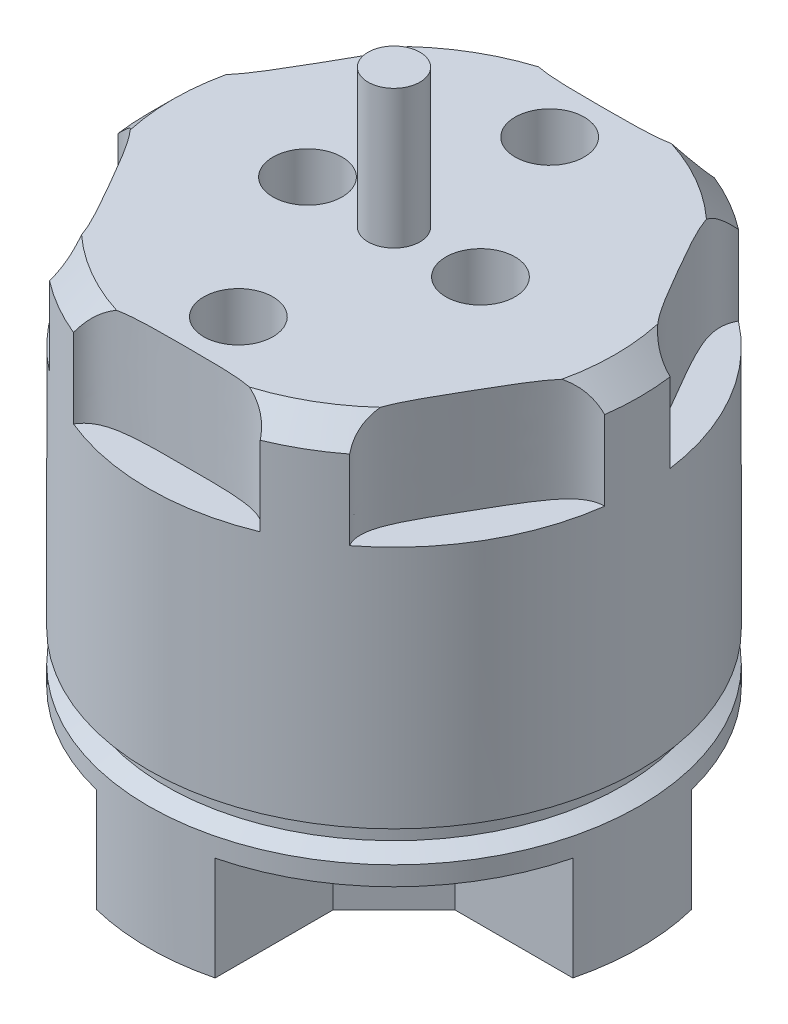
SolidWorks part; units mm, degrees
material "ABS PC"
ref_plane "Front Plane" through (0, 0, 0) normal (0, 0, 1) x (1, 0, 0)
ref_plane "Top Plane" through (0, 0, 0) normal (0, 1, 0) x (1, 0, 0)
ref_plane "Right Plane" through (0, 0, 0) normal (1, 0, 0) x (0, 0, -1)
sketch "Sketch1" plane through (0, 0, 0) normal (1, 0, 0) x (0, 0, -1)
  line L0 (0, 0) -> (0, 18.5) construction
  line L1 (0, 18.5) -> (-0.75, 18.5)
  line L2 (-0.75, 18.5) -> (-0.75, 14.5)
  line L3 (-0.75, 14.5) -> (-6.3929, 14.5)
  line L4 (-7.1, 13.7929) -> (-6.3929, 14.5)
  line L5 (-7.1, 13.7929) -> (-7.1, 14.5) construction
  line L6 (-7.1, 14.5) -> (-6.3929, 14.5) construction
  line L7 (-7.1, 14.5) -> (-6.7464, 14.1464) construction
  line L8 (-7.1, 13.7929) -> (-7.1, 0)
  line L9 (-7.1, 0) -> (-1, 0)
  line L10 (-1, 0) -> (-1, -1)
  line L11 (-1, -1) -> (0, -1)
  line L12 (0, -1) -> (0, 0)
  line L13 (0, 0) -> (0, 18.5)
  point P9 (-1, -0.5)
  dimension "D1" = 1.5
  dimension "D2" = 4
  dimension "D3" = 18.5
  dimension "D4" = 14.2
  dimension "D5" = 0.5
  dimension "D6" = 2
  dimension "D7" = 1
revolve "Revolve1" add sketch "Sketch1" angle 360 about L13
sketch "Sketch2" plane through (0, 0, 0) normal (0, 0, 1) x (1, 0, 0)
  line L0 (-7.1, 4) -> (7.1, 4)
  line L1 (-7.1, 13.7929) -> (-7.1, 0) construction
  line L2 (7.1, 0) -> (7.1, 13.7929) construction
  dimension "D1" = 4
split line "Split Line1"
sketch "Sketch3" plane through (0, 0, 0) normal (0, -1, 0) x (1, 0, 0)
  circle A5 centre (0, 0) radius 4.5 construction
  circle A6 centre (0, 4.5) radius 1
  circle A7 centre (4.5, 0) radius 1
  circle A8 centre (-4.5, 0) radius 1
  circle A9 centre (0, -4.5) radius 1
  dimension "D1" = 2
  dimension "D2" = 9
extrude "Cut-Extrude1" cut sketch "Sketch3" against normal blind 3
sketch "Sketch4" plane through (0, 14.5, 0) normal (0, 1, 0) x (1, 0, 0)
  line L0 (-2.5, 0) -> (0, 0) construction
  line L1 (0, 0) -> (0, 4.5) construction
  circle A0 centre (0, 4.5) radius 1
  circle A1 centre (2.5, 0) radius 1
  circle A2 centre (0, -4.5) radius 1
  circle A3 centre (-2.5, 0) radius 1
  ellipse E0 centre (0, 0) end of major axis (0, 4.5) minor radius 2.5 construction
  dimension "D3" = 2
  dimension "D1" = 5
  dimension "D2" = 9
extrude "Cut-Extrude2" cut sketch "Sketch4" against normal blind 4
sketch "Sketch5" plane through (0, 14.5, 0) normal (0, 1, 0) x (1, 0, 0)
  line L0 (-2.7, 6.5666) -> (-2.0712, 5.5) construction
  line L1 (-2.0712, 5.5) -> (0, 6.5) construction
  line L2 (0, 6.5) -> (2.0712, 5.5) construction
  line L3 (2.0712, 5.5) -> (2.7, 6.5666) construction
  line L4 (0, 0) -> (0, 6.5) construction
  line L5 (-2.0712, 5.5) -> (0, 5.5) construction
  line L6 (0, 5.5) -> (2.0712, 5.5) construction
  line L7 (-2.7, 6.5666) -> (0, 6.5666) construction
  line L8 (0, 6.5666) -> (2.7, 6.5666) construction
  line L9 (4.3368, 5.6216) -> (3.7275, 4.5437) construction
  line L10 (3.7275, 4.5437) -> (5.6292, 3.25) construction
  line L11 (5.6292, 3.25) -> (5.7988, 0.9563) construction
  line L12 (5.7988, 0.9563) -> (7.0368, 0.945) construction
  line L13 (7.0368, -0.945) -> (5.7988, -0.9563) construction
  line L14 (5.7988, -0.9563) -> (5.6292, -3.25) construction
  line L15 (5.6292, -3.25) -> (3.7275, -4.5437) construction
  line L16 (3.7275, -4.5437) -> (4.3368, -5.6216) construction
  line L17 (2.7, -6.5666) -> (2.0712, -5.5) construction
  line L18 (2.0712, -5.5) -> (0, -6.5) construction
  line L19 (0, -6.5) -> (-2.0712, -5.5) construction
  line L20 (-2.0712, -5.5) -> (-2.7, -6.5666) construction
  line L21 (-4.3368, -5.6216) -> (-3.7275, -4.5437) construction
  line L22 (-3.7275, -4.5437) -> (-5.6292, -3.25) construction
  line L23 (-5.6292, -3.25) -> (-5.7988, -0.9563) construction
  line L24 (-5.7988, -0.9563) -> (-7.0368, -0.945) construction
  line L25 (-7.0368, 0.945) -> (-5.7988, 0.9563) construction
  line L26 (-5.7988, 0.9563) -> (-5.6292, 3.25) construction
  line L27 (-5.6292, 3.25) -> (-3.7275, 4.5437) construction
  line L28 (-3.7275, 4.5437) -> (-4.3368, 5.6216) construction
  circle A0 centre (0, 0) radius 6 construction
  circle A1 centre (0, 0) radius 7.1 construction
  circle A2 centre (0, 4.5) radius 1 construction
  circle A3 centre (0, 4.5) radius 1 construction
  arc A4 (-2.7, 6.5666) -> (2.7, 6.5666) centre (0, 0) cw
  arc A5 (4.3368, 5.6216) -> (7.0368, 0.945) centre (0, 0) cw
  arc A6 (7.0368, -0.945) -> (4.3368, -5.6216) centre (0, 0) cw
  arc A7 (2.7, -6.5666) -> (-2.7, -6.5666) centre (0, 0) cw
  arc A8 (-4.3368, -5.6216) -> (-7.0368, -0.945) centre (0, 0) cw
  arc A9 (-7.0368, 0.945) -> (-4.3368, 5.6216) centre (0, 0) cw
  spline S0 degree 4 poles (-2.7, 6.5666) (-2.0712, 5.5) (0, 6.5) (2.0712, 5.5) (2.7, 6.5666) knots 0 0 0 0 0 1 1 1 1 1
  spline S1 degree 4 poles (4.3368, 5.6216) (3.7275, 4.5437) (5.6292, 3.25) (5.7988, 0.9563) (7.0368, 0.945) knots 0 0 0 0 0 1 1 1 1 1
  spline S2 degree 4 poles (7.0368, -0.945) (5.7988, -0.9563) (5.6292, -3.25) (3.7275, -4.5437) (4.3368, -5.6216) knots 0 0 0 0 0 1 1 1 1 1
  spline S3 degree 4 poles (2.7, -6.5666) (2.0712, -5.5) (0, -6.5) (-2.0712, -5.5) (-2.7, -6.5666) knots 0 0 0 0 0 1 1 1 1 1
  spline S4 degree 4 poles (-4.3368, -5.6216) (-3.7275, -4.5437) (-5.6292, -3.25) (-5.7988, -0.9563) (-7.0368, -0.945) knots 0 0 0 0 0 1 1 1 1 1
  spline S5 degree 4 poles (-7.0368, 0.945) (-5.7988, 0.9563) (-5.6292, 3.25) (-3.7275, 4.5437) (-4.3368, 5.6216) knots 0 0 0 0 0 1 1 1 1 1
  point P47 (0, 0)
  dimension "D1" = 12
  dimension "D2" = 6.5
  dimension "D3" = 2.7
  dimension "D4" = 2.3
  dimension "D5" = 6
extrude "Cut-Extrude3" cut sketch "Sketch5" against normal blind 3
sketch "Sketch6" plane through (0, 0, 0) normal (0, -1, 0) x (1, 0, 0)
  line L0 (5.0205, -5.0205) -> (-5.0205, 5.0205) construction
  line L1 (-4.5, 0) -> (-2.25, 2.25) construction
  line L2 (-2.25, 2.25) -> (0, 4.5) construction
  line L3 (-1.7184, 6.8889) -> (-1.7184, 3.4862)
  line L4 (-1.7184, 3.4862) -> (-3.4862, 1.7184)
  line L5 (-3.4862, 1.7184) -> (-6.8889, 1.7184)
  line L6 (1.7184, 3.4862) -> (1.7184, 6.8889)
  line L7 (6.8889, 1.7184) -> (3.4862, 1.7184)
  line L8 (3.4862, 1.7184) -> (1.7184, 3.4862)
  line L9 (3.4862, -1.7184) -> (6.8889, -1.7184)
  line L10 (1.7184, -6.8889) -> (1.7184, -3.4862)
  line L11 (1.7184, -3.4862) -> (3.4862, -1.7184)
  line L12 (-1.7184, -3.4862) -> (-1.7184, -6.8889)
  line L13 (-6.8889, -1.7184) -> (-3.4862, -1.7184)
  line L14 (-3.4862, -1.7184) -> (-1.7184, -3.4862)
  circle A0 centre (0, 0) radius 7.1 construction
  arc A1 (-1.7184, 6.8889) -> (-6.8889, 1.7184) centre (0, 0) ccw
  arc A2 (6.8889, 1.7184) -> (1.7184, 6.8889) centre (0, 0) ccw
  arc A3 (1.7184, -6.8889) -> (6.8889, -1.7184) centre (0, 0) ccw
  arc A4 (-6.8889, -1.7184) -> (-1.7184, -6.8889) centre (0, 0) ccw
  point P8 (-2.6023, 2.6023)
  point P35 (0, 0)
  dimension "D1" = 3.4027
  dimension "D2" = 2.5
  dimension "D3" = 4
extrude "Cut-Extrude4" cut sketch "Sketch6" against normal blind 3
sketch "Sketch7" plane through (0, 0, 0) normal (1, 0, 0) x (0, 0, -1)
  line L0 (0, 0) -> (0, 18.5) construction
  line L1 (0.75, 18.5) -> (-0.75, 18.5) construction
  line L2 (-7.1, 3.55) -> (-6.6, 3.8)
  line L3 (-7.1, 4) -> (-7.1, 0) construction
  line L4 (-6.6, 3.8) -> (-6.6, 4.2)
  line L5 (-6.6, 4.2) -> (-7.1, 4.45)
  line L6 (-7.1, 11.5) -> (-7.1, 4) construction
  line L7 (-7.1, 4.45) -> (-7.1, 3.55)
  line L8 (0, 4) -> (-6.6, 4) construction
  line L9 (-6.6, 4) -> (-7.1, 4) construction
  line L10 (-7.1, 4) -> (0, 4) construction
  dimension "D1" = 0.4
  dimension "D2" = 0.9
  dimension "D3" = 0.5
revolve "Cut-Revolve1" cut sketch "Sketch7" angle 360 about L0
